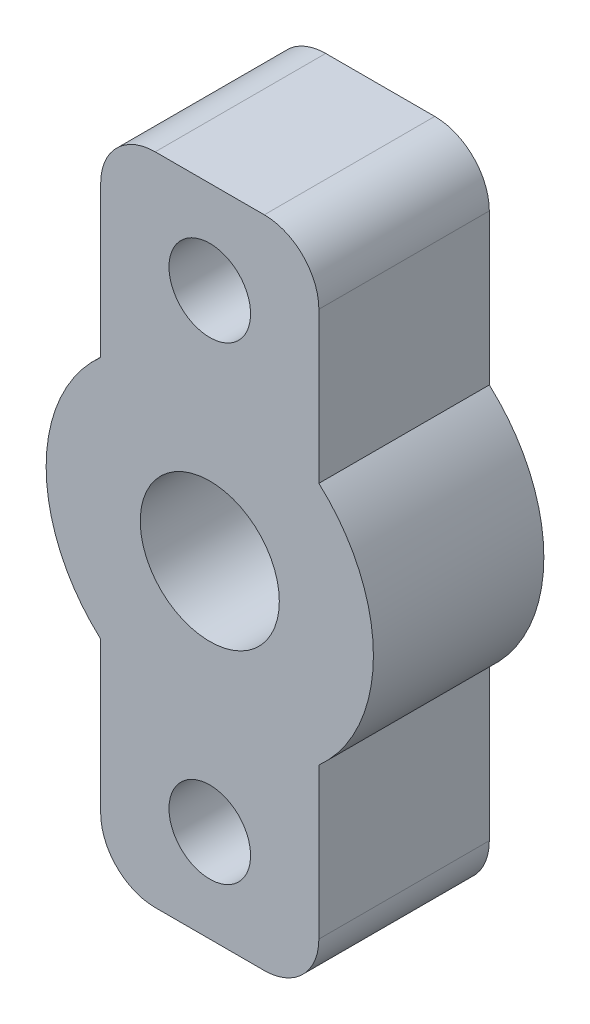
SolidWorks part; units mm, degrees
ref_plane "前视基准面" through (0, 0, 0) normal (0, 0, 1) x (1, 0, 0)
ref_plane "上视基准面" through (0, 0, 0) normal (0, 1, 0) x (1, 0, 0)
ref_plane "右视基准面" through (0, 0, 0) normal (1, 0, 0) x (0, 0, -1)
sketch "草图1" plane through (0, 0, 0) normal (0, 0, 1) x (1, 0, 0)
  line L0 (-5.08, 12.7) -> (-5.08, 5.6796)
  line L1 (-2.54, 15.24) -> (2.54, 15.24)
  line L2 (5.08, 12.7) -> (5.08, 5.6796)
  line L3 (0, 0) -> (0, 27.9989) construction
  line L4 (0, 0) -> (25.2898, 0) construction
  line L5 (5.08, -12.7) -> (5.08, -5.6796)
  line L6 (-2.54, -15.24) -> (2.54, -15.24)
  line L7 (-5.08, -12.7) -> (-5.08, -5.6796)
  arc A0 (-5.08, 5.6796) -> (-5.08, -5.6796) centre (0, 0) ccw
  arc A1 (5.08, 12.7) -> (2.54, 15.24) centre (2.54, 12.7) ccw
  arc A2 (-2.54, 15.24) -> (-5.08, 12.7) centre (-2.54, 12.7) ccw
  arc A3 (5.08, -12.7) -> (2.54, -15.24) centre (2.54, -12.7) cw
  arc A4 (-2.54, -15.24) -> (-5.08, -12.7) centre (-2.54, -12.7) cw
  arc A5 (5.08, -5.6796) -> (5.08, 5.6796) centre (0, 0) ccw
  dimension "D1" = 15.24
  dimension "D5" = 2.54
  dimension "D2" = 10.16
  dimension "D3" = 5.08
  dimension "D4" = 15.24
extrude "凸台-拉伸1" add sketch "草图1" along normal blind 7.9375
sketch "草图4" plane through (0, 0, 0) normal (0, 0, -1) x (-1, 0, 0)
  circle A0 centre (0, 10.922) radius 1.9
  dimension "D1" = 3.8
  dimension "D2" = 10.922
extrude "切除-拉伸3" cut sketch "草图4" against normal through all
ref_plane "基准面1" through (0, 0, 0) normal (0, 1, 0) x (1, 0, 0)
mirror "镜向1" about plane through (0, 0, 0) normal (0, 1, 0) of "切除-拉伸3"
sketch "草图5" plane through (0, 0, 7.9375) normal (0, 0, 1) x (1, 0, 0)
  circle A0 centre (0, 0) radius 3.2385
  dimension "D1" = 6.477
extrude "切除-拉伸4" cut sketch "草图5" against normal through all
